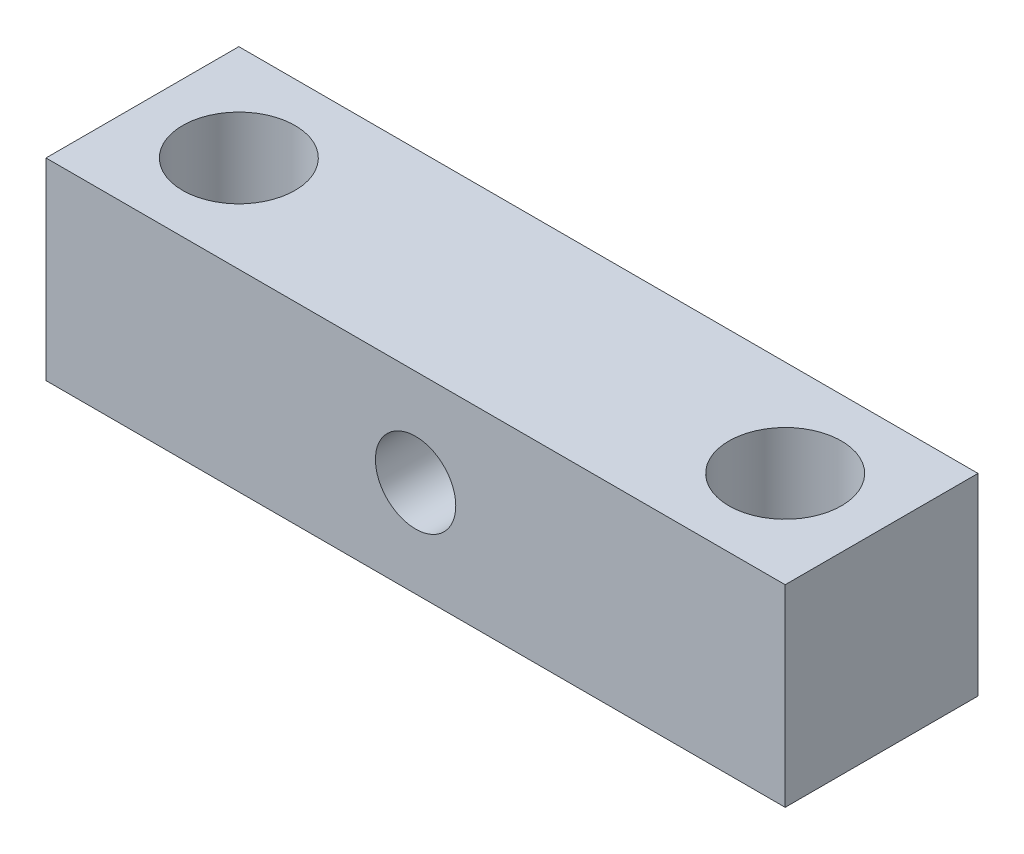
SolidWorks part; units mm, degrees
ref_plane "Front" through (0, 0, 0) normal (0, 0, 1) x (1, 0, 0)
ref_plane "Top" through (0, 0, 0) normal (0, 1, 0) x (1, 0, 0)
ref_plane "Right" through (0, 0, 0) normal (1, 0, 0) x (0, 0, -1)
sketch "Sketch1" plane through (0, 0, 0) normal (0, 1, 0) x (1, 0, 0)
  line L0 (0, -10.2265) -> (0, 21.0843) construction
  line L1 (-23, 12) -> (23, 12)
  line L2 (-23, 12) -> (-23, 0)
  line L3 (-23, 0) -> (23, 0)
  line L4 (23, 12) -> (23, 0)
  dimension "D1" = 12
  dimension "D2" = 46
extrude "Boss-Extrude1" add sketch "Sketch1" along normal blind 12
hole_wizard "Ø7.0 (7) Diameter Hole1" positions "Sketch3" profile "Sketch2" hole size "Ø7.0" standard "JIS" end condition up to next
sketch "Sketch3" plane through (-8.628, 12, -9.0449) normal (0, -1, 0) x (1, 0, 0)
  line L0 (8.628, -1.3213) -> (8.628, 9.3489) construction
  line L3 (-14.372, 9.0449) -> (31.628, 9.0449) construction
  point P0 (25.628, 3.0449)
  point P1 (-8.372, 3.0449)
  dimension "D1" = 6
  dimension "D2" = 34
sketch "Sketch2" plane through (17, 12, -6) normal (1, 0, 0) x (0, 0, 1)
  line L0 (0, 0) -> (0, 12)
  line L1 (0, 12) -> (3.5, 12)
  line L2 (3.5, 12) -> (3.5, 0)
  line L5 (3.5, 0) -> (0, 0)
  line L11 (0, -6.35) -> (0, 107.95) construction
  dimension "Thru Hole Dia." = 7
  dimension "Thru Hole Depth" = 12
hole_wizard "M6x1.0 Tapped Hole1" positions "Sketch5" profile "Sketch4" tap size "M6x1.0" standard "JIS" end condition up to next
sketch "Sketch5" plane through (0, 0, 0) normal (0, 0, 1) x (1, 0, 0)
  line L0 (-23, 0) -> (23, 0) construction
  point P0 (0, 6)
  dimension "D1" = 6
sketch "Sketch4" plane through (0, 6, 0) normal (1, 0, 0) x (0, -1, 0)
  line L0 (0, 0) -> (0, 12)
  line L1 (0, 12) -> (2.5, 12)
  line L2 (2.5, 12) -> (2.5, 0)
  line L5 (2.5, 0) -> (0, 0)
  line L11 (0, -6.35) -> (0, 107.95) construction
  dimension "Thru Tap Drill Dia." = 5
  dimension "Thru Tap Drill Depth" = 12
cosmetic thread "Hole Thread1"
